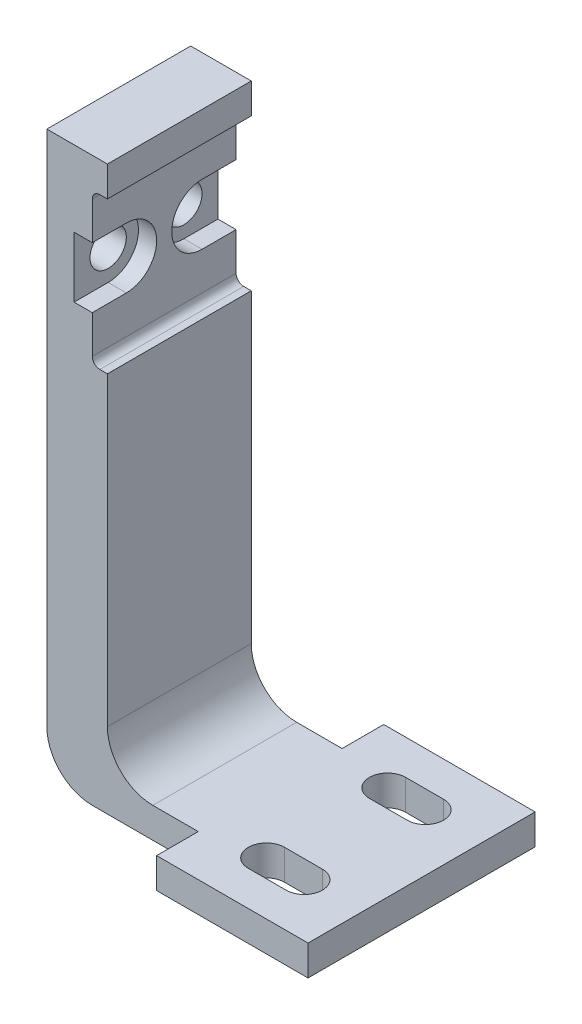
SolidWorks part; units mm, degrees
material "6061-T6 (SS)"
ref_plane "Front Plane" through (0, 0, 0) normal (0, 0, 1) x (1, 0, 0)
ref_plane "Top Plane" through (0, 0, 0) normal (0, 1, 0) x (1, 0, 0)
ref_plane "Right Plane" through (0, 0, 0) normal (1, 0, 0) x (0, 0, -1)
sketch "Sketch1" plane through (0, 0, 0) normal (0, 0, 1) x (1, 0, 0)
  line L0 (-14.4886, 22.07) -> (-16.5374, 22.07) construction
  line L9 (-16.5374, 17.07) -> (-16.5374, 27.07)
  line L10 (-19.5374, 0) -> (-19.5374, 29.07)
  line L11 (-19.5374, 29.07) -> (-15.5374, 29.07)
  line L12 (-15.5374, 29.07) -> (-15.5374, 27.07)
  line L17 (-15.4274, -6.11) -> (0.4626, -6.11)
  line L18 (0.4626, -6.11) -> (0.4626, -8.11)
  line L19 (0.4626, -8.11) -> (-11.4274, -8.11)
  line L20 (-16.5374, 27.07) -> (-15.5374, 27.07)
  line L21 (-16.5374, 17.07) -> (-15.5374, 17.07)
  line L22 (-15.5374, 17.07) -> (-15.5374, 14.07)
  line L23 (-19.5374, 0) -> (-19.5374, -8.11)
  line L24 (-19.5374, -8.11) -> (-11.4274, -8.11)
  line L25 (-15.5374, 14.07) -> (-15.5374, -6.11)
  line L26 (-15.5374, -6.11) -> (-15.4274, -6.11)
  line L29 (-15.4274, -6.11) -> (-13.0144, -6.11) construction
  point P15 (-16.5374, 22.07)
  point P21 (-12.4274, 0)
  dimension "D3" = 37.18
  dimension "D4" = 3
  dimension "D2" = 4
  dimension "D5" = 20
  dimension "D6" = 10
  dimension "D7" = 2
  dimension "D8" = 1
  dimension "D10" = 2
extrude "Boss-Extrude1" add sketch "Sketch1" along normal mid plane 9.5
sketch "Sketch2" plane through (-16.5374, 0, 0) normal (1, 0, 0) x (0, 0, -1)
  line L0 (-4.75, 22.07) -> (4.75, 22.07) construction
  line L1 (-4.75, 17.07) -> (-4.75, 27.07) construction
  line L2 (4.75, 17.07) -> (4.75, 27.07) construction
  point P8 (-2.5, 22.07)
  point P9 (0, 22.07)
  point P11 (2.5, 22.07)
  dimension "D2" = 2.5
  dimension "D1" = 2.5
hole_wizard "M2 Clearance Hole1" positions "3DSketch1" profile "Sketch3" hole size "M2" standard "ANSI Metric" end condition through all
sketch3d "3DSketch1"
  point P0 (-16.5374, 22.07, 2.5)
  point P3 (-16.5374, 22.07, -2.5)
sketch "Sketch3" plane through (-16.5374, 22.07, 2.5) normal (0, 1, 0) x (0, 0, -1)
  line L0 (0, 0) -> (0, 3)
  line L1 (0, 3) -> (1.2, 3)
  line L2 (1.2, 3) -> (1.2, 0)
  line L5 (1.2, 0) -> (0, 0)
  line L11 (0, -6.35) -> (0, 107.95) construction
  dimension "Thru Hole Dia." = 2.4
  dimension "Thru Hole Depth" = 3
sketch "Sketch4" plane through (-16.5374, 0, 0) normal (1, 0, 0) x (0, 0, -1)
  line L0 (-2.5, 24.07) -> (-4.75, 24.07)
  line L1 (-4.75, 17.07) -> (-4.75, 27.07) construction
  line L2 (-4.75, 24.07) -> (-4.75, 20.07)
  line L3 (-4.75, 20.07) -> (-2.5, 20.07)
  line L4 (0, 55) -> (0, -55) construction
  line L5 (4.75, 20.07) -> (2.5, 20.07)
  line L6 (4.75, 24.07) -> (4.75, 20.07)
  line L7 (2.5, 24.07) -> (4.75, 24.07)
  arc A0 (-2.5, 20.07) -> (-2.5, 24.07) centre (-2.5, 22.07) ccw
  arc A1 (2.5, 24.07) -> (2.5, 20.07) centre (2.5, 22.07) ccw
  dimension "D1" = 4
  dimension "D2" = 4
extrude "Cut-Extrude1" cut sketch "Sketch4" against normal blind 1.2
sketch "Sketch5" plane through (0, -8.11, 0) normal (0, -1, 0) x (1, 0, 0)
  line L0 (0.4626, -7.5) -> (0.4626, 7.5)
  line L1 (0.4626, 4.75) -> (0.4626, -4.75) construction
  line L2 (0.4626, 7.5) -> (-9.5374, 7.5)
  line L3 (-9.5374, 7.5) -> (-9.5374, -7.5)
  line L4 (-9.5374, -7.5) -> (0.4626, -7.5)
  point P3 (0.4626, 0)
  dimension "D1" = 10
  dimension "D2" = 15
extrude "Boss-Extrude2" add sketch "Sketch5" against normal blind 2
sketch "Sketch6" plane through (0, -6.11, 0) normal (0, 1, 0) x (1, 0, 0)
  line L0 (0.4626, 0) -> (-9.5374, 0) construction
  line L1 (0.4626, 7.5) -> (0.4626, -7.5) construction
  line L2 (-3.2874, -4) -> (-5.7874, -4) construction
  line L3 (-4.5374, -7.5) -> (-4.5374, 7.5) construction
  line L4 (0.4626, -7.5) -> (-9.5374, -7.5) construction
  line L5 (-9.5374, 7.5) -> (0.4626, 7.5) construction
  line L6 (-3.2874, -5.2) -> (-5.7874, -5.2)
  line L7 (-3.2874, -2.8) -> (-5.7874, -2.8)
  line L8 (-3.2874, 4) -> (-5.7874, 4) construction
  line L9 (-3.2874, 5.2) -> (-5.7874, 5.2)
  line L10 (-3.2874, 2.8) -> (-5.7874, 2.8)
  arc A0 (-3.2874, -5.2) -> (-3.2874, -2.8) centre (-3.2874, -4) ccw
  arc A1 (-5.7874, -2.8) -> (-5.7874, -5.2) centre (-5.7874, -4) ccw
  arc A2 (-3.2874, 5.2) -> (-3.2874, 2.8) centre (-3.2874, 4) cw
  arc A3 (-5.7874, 2.8) -> (-5.7874, 5.2) centre (-5.7874, 4) cw
  point P12 (-4.5374, -4)
  point P13 (-4.5374, 0)
  point P14 (-4.5374, 4)
  point P15 (-4.5374, -4)
  point P23 (-4.5374, 4)
  dimension "D3" = 1.2
  dimension "D1" = 4
  dimension "D2" = 2.5
extrude "Cut-Extrude2" cut sketch "Sketch6" against normal up to surface (2 mm away) up to face at (-9.5374, -8.11, 0)
fillet "Fillet1" radius 3 2 edges at (-15.5374, -6.11, 0) (-19.5374, -8.11, 0)
fillet "Fillet2" radius 0.5 2 edges at (-16.5374, 17.07, 0) (-16.5374, 27.07, 0)
